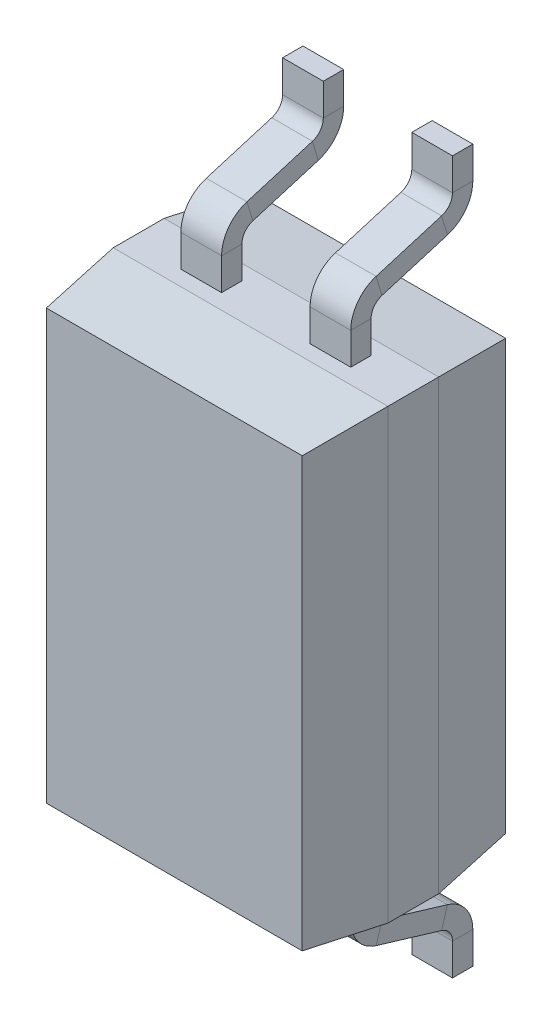
SolidWorks part; units mm, degrees
ref_plane "前视基准面" through (0, 0, 0) normal (0, 0, 1) x (1, 0, 0)
ref_plane "上视基准面" through (0, 0, 0) normal (0, 1, 0) x (1, 0, 0)
ref_plane "右视基准面" through (0, 0, 0) normal (1, 0, 0) x (0, 0, -1)
sketch "草图1" plane through (0, 0, 0) normal (0, 0, 1) x (1, 0, 0)
  line L1 (-1.35, -2.2) -> (1.35, -2.2)
  line L2 (-1.35, -2.2) -> (-1.35, 2.2)
  line L3 (-1.35, 2.2) -> (1.35, 2.2)
  line L4 (1.35, -2.2) -> (1.35, 2.2)
  line L5 (-1.35, -2.2) -> (1.35, 2.2) construction
  line L6 (-1.35, 2.2) -> (1.35, -2.2) construction
  point P0 (0, 0)
  dimension "D1" = 4.4
  dimension "D2" = 2.7
extrude "凸台-拉伸1" add sketch "草图1" along normal blind 2
chamfer "倒角1" distance 0.75 angle 7 8 edges at (0, 2.2, 0) (-1.35, 0, 0) (0, -2.2, 0) (1.35, 0, 0) (0, -2.2, 2) (-1.35, 0, 2) (0, 2.2, 2) (1.35, 0, 2)
sketch "草图2" plane through (0, -2.2, 0) normal (0, -1, 0) x (1, 0, 0)
  line L0 (-1.35, 1) -> (1.35, 1) construction
  line L1 (-1.35, 1.25) -> (-1.35, 0.75) construction
  line L2 (1.35, 1.25) -> (1.35, 0.75) construction
  line L4 (0.435, 0.9) -> (0.835, 0.9)
  line L5 (0.435, 0.9) -> (0.435, 1.1)
  line L6 (0.435, 1.1) -> (0.835, 1.1)
  line L7 (0.835, 0.9) -> (0.835, 1.1)
  line L8 (0.435, 0.9) -> (0.835, 1.1) construction
  line L9 (0.435, 1.1) -> (0.835, 0.9) construction
  point P6 (0, 1)
  point P7 (0.635, 1)
  dimension "D1" = 0.635
  dimension "D2" = 0.4
  dimension "D3" = 0.2
sketch "草图3" plane through (0, 0, 0) normal (1, 0, 0) x (0, 0, -1)
  line L0 (-1, -2.2) -> (0, -2.2) construction
  line L1 (0, 2.1079) -> (0, -2.1079) construction
  line L2 (0, -3.5) -> (0, -3.186)
  line L3 (-1, -2.2) -> (-1, -2.514)
  line L4 (-0.8218, -2.7534) -> (-0.1782, -2.9466)
  arc A0 (0, -3.186) -> (-0.1782, -2.9466) centre (-0.25, -3.186) ccw
  arc A1 (-1, -2.514) -> (-0.8218, -2.7534) centre (-0.75, -2.514) ccw
  point P6 (0, -3.5)
  point P12 (0, -3)
  point P15 (-1, -2.7)
  dimension "D4" = 0.25
  dimension "D1" = 3.5
  dimension "D2" = 0.5
  dimension "D3" = 0.5
sweep "扫描1" add profiles "草图2" path "草图3"
pattern_linear "阵列(线性)1" count 2 spacing 1.27 along (-1, 0, 0) of "扫描1"
mirror "镜向1" about plane through (0, 0, 0) normal (0, 1, 0) of "阵列(线性)1", "扫描1"
equation "\"D1@草图2\"=1.27/2"
equation "\"D1@草图3\"=7/2"
